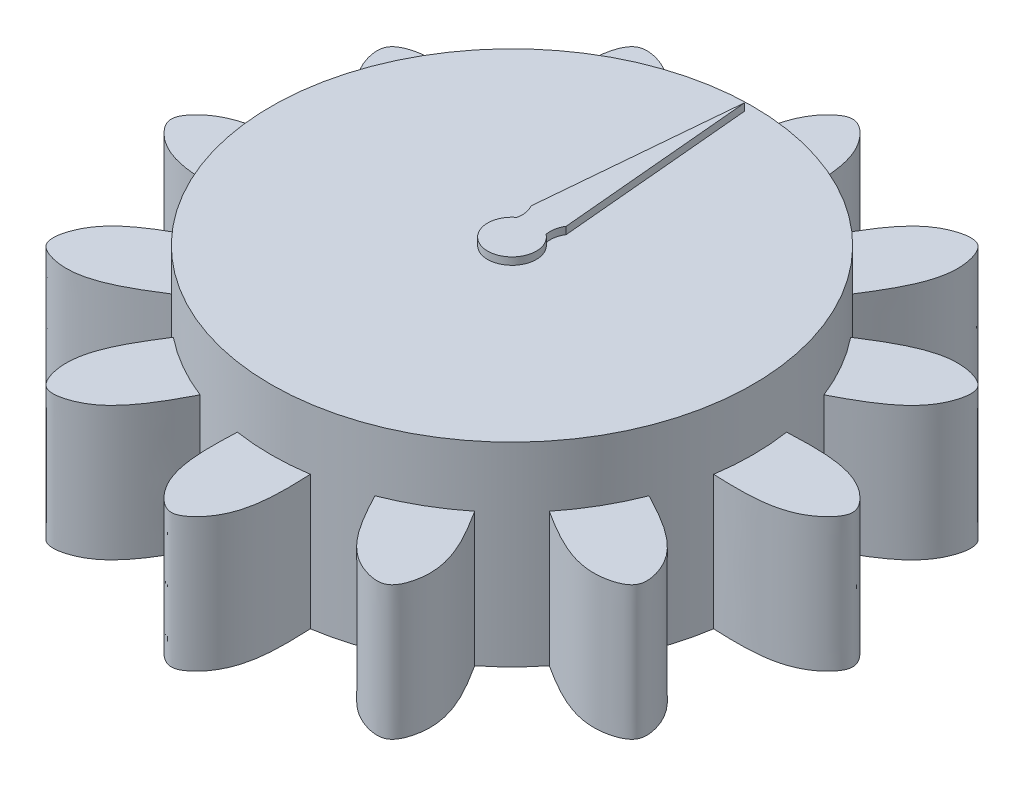
SolidWorks part; units mm, degrees
ref_plane "Front Plane" through (0, 0, 0) normal (0, 0, 1) x (1, 0, 0)
ref_plane "Top Plane" through (0, 0, 0) normal (0, 1, 0) x (1, 0, 0)
ref_plane "Right Plane" through (0, 0, 0) normal (1, 0, 0) x (0, 0, -1)
sketch "Sketch1" plane through (0, 0, 0) normal (0, 1, 0) x (1, 0, 0)
  line L0 (0, 0) -> (0, 10) construction
  circle A12 centre (0, 0) radius 9.9
  point P43 (0, 0)
  dimension "D1" = 19.8
extrude "Boss-Extrude1" add sketch "Sketch1" along normal blind 6
sketch "Sketch4" plane through (0, 0, 0) normal (0, -1, 0) x (1, 0, 0)
  line L0 (-1.5, -9.7857) -> (1.5, -9.7857)
  circle A1 centre (0, 0) radius 9.9 construction
  spline S0 degree 3 poles (1.5, -9.7857) (1.5223, -10.3509) (1.5744, -11.6677) (1.1993, -13.2812) (0, -14.189) (-1.1993, -13.2812) (-1.5744, -11.6677) (-1.5223, -10.3509) (-1.5, -9.7857) knots 0 0 0 0 0.178316 0.415433 0.5 0.584567 0.821684 1 1 1 1
  dimension "D1" = 3
  dimension "D2" = 3
  dimension "D3" = 14
  dimension "D4" = 1.4
  dimension "D5" = 0.4
  dimension "D6" = 0.7
  dimension "D7" = 1.7
  dimension "D8" = 4.2143
sketch "Sketch2" plane through (0, 6, 0) normal (0, 1, 0) x (1, 0, 0)
  circle A0 centre (0, 0) radius 9.9
  dimension "D1" = 19.8
extrude "Boss-Extrude2" add sketch "Sketch2" along normal blind 2
sketch "Sketch3" plane through (0, 8, 0) normal (0, 1, 0) x (1, 0, 0)
  line L0 (0, 0) -> (0, 1) construction
  line L2 (0, 1) -> (0, 9.5619) construction
  line L3 (0, 9.5619) -> (0.7279, 1.5)
  line L4 (0, 9.5619) -> (-0.7174, 1.5002)
  arc A0 (-0.6, 0.8) -> (0.6, 0.8) centre (0, 0) ccw
  arc A1 (0.7279, 1.5) -> (0.6, 0.8) centre (1.5527, 0.9877) ccw
  arc A2 (-0.7174, 1.5002) -> (-0.6, 0.8) centre (-1.55, 1.0007) cw
  point P6 (0.7279, 1.5)
  dimension "D1" = 2
  dimension "D3" = 0.971
  dimension "D6" = 8.5619
  dimension "D2" = 1.2
  dimension "D4" = 0.7116
  dimension "D5" = 0.71
  dimension "D7" = 0.9527
  dimension "D8" = 0.95
  dimension "D9" = 1.8402
extrude "Boss-Extrude3" add sketch "Sketch3" along normal blind 0.3 contours A1 A0 A2 L4 L3
extrude "Boss-Extrude5" add sketch "Sketch4" against normal blind 5.5
pattern_circular "CirPattern1" count 12 over 360 about axis through (0, 0, 0) along (0, 1, 0) of "Boss-Extrude5"
